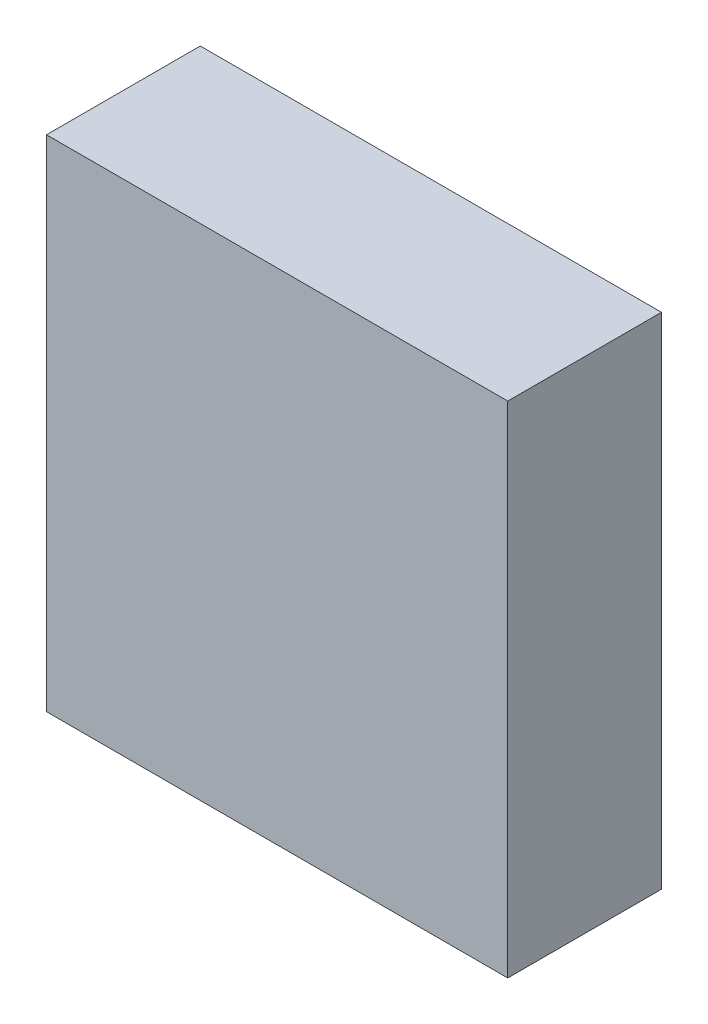
SolidWorks part; units mm, degrees
ref_plane "Front Plane" through (0, 0, 0) normal (0, 0, 1) x (1, 0, 0)
ref_plane "Top Plane" through (0, 0, 0) normal (0, 1, 0) x (1, 0, 0)
ref_plane "Right Plane" through (0, 0, 0) normal (1, 0, 0) x (0, 0, -1)
sketch "Sketch2" plane through (0, 0, 0) normal (0, 1, 0) x (1, 0, 0)
  line L1 (0, 0) -> (1828.8, 0)
  line L2 (0, 0) -> (0, 609.6)
  line L3 (0, 609.6) -> (1828.8, 609.6)
  line L4 (1828.8, 0) -> (1828.8, 609.6)
  dimension "D1" = 609.6
  dimension "D2" = 1828.8
extrude "Boss-Extrude1" add sketch "Sketch2" along normal blind 1981.2
